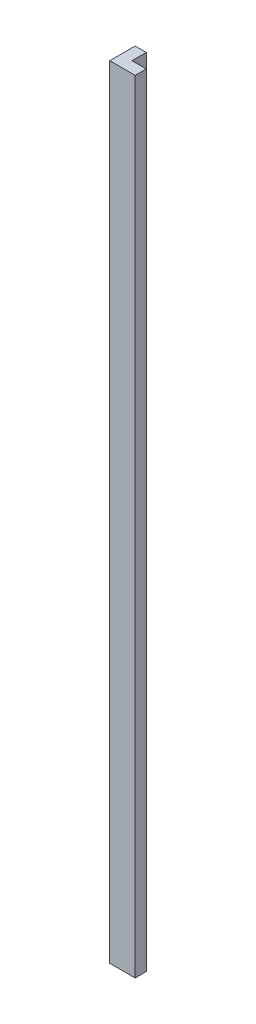
SolidWorks part; units mm, degrees
ref_plane "Front" through (0, 0, 0) normal (0, 0, 1) x (1, 0, 0)
ref_plane "Top" through (0, 0, 0) normal (0, 1, 0) x (1, 0, 0)
ref_plane "Right" through (0, 0, 0) normal (1, 0, 0) x (0, 0, -1)
sketch "Sketch1" plane through (0, 0, 0) normal (0, 1, 0) x (1, 0, 0)
  line L0 (0, 0) -> (0, 231.775)
  line L1 (0, 231.775) -> (101.6, 231.775)
  line L2 (101.6, 231.775) -> (101.6, 101.6)
  line L3 (101.6, 101.6) -> (231.775, 101.6)
  line L4 (231.775, 101.6) -> (231.775, 0)
  line L5 (231.775, 0) -> (0, 0)
  dimension "D1" = 101.6
  dimension "D2" = 231.775
extrude "Boss-Extrude1" add sketch "Sketch1" along normal blind 7124.7
